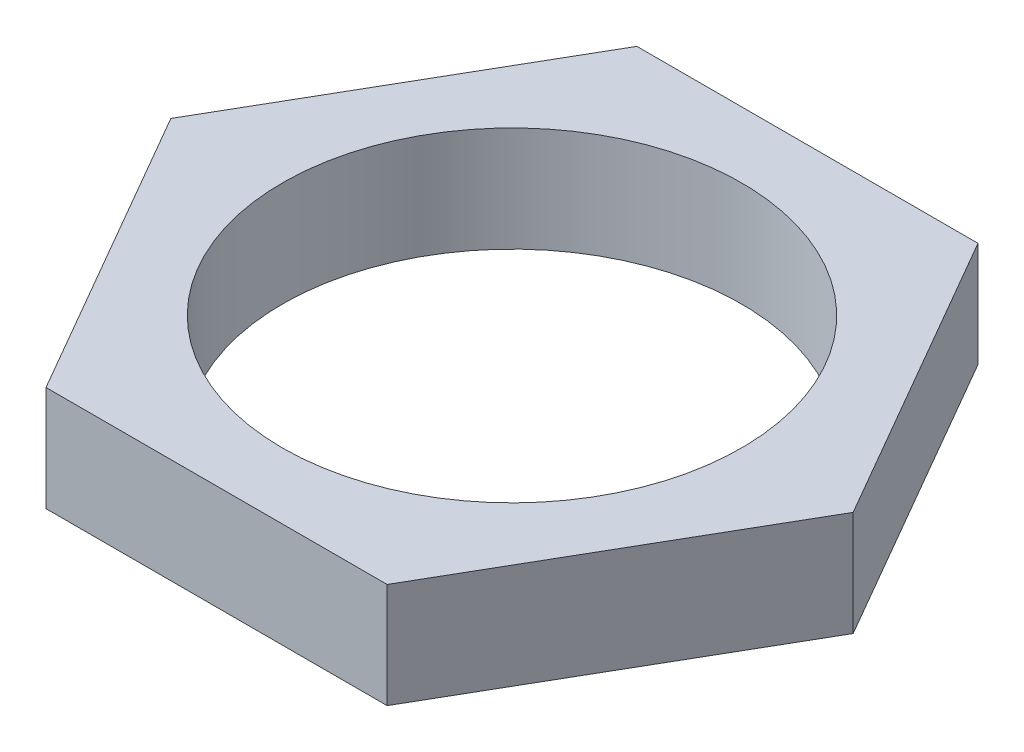
SolidWorks part; units mm, degrees
material "6061-T6 (SS)"
ref_plane "Front Plane" through (0, 0, 0) normal (0, 0, 1) x (1, 0, 0)
ref_plane "Top Plane" through (0, 0, 0) normal (0, 1, 0) x (1, 0, 0)
ref_plane "Right Plane" through (0, 0, 0) normal (1, 0, 0) x (0, 0, -1)
sketch "Sketch1" plane through (0, 0, 0) normal (0, 1, 0) x (1, 0, 0)
  line L1 (4.1275, -7.149) -> (8.255, 0)
  line L2 (8.255, 0) -> (4.1275, 7.149)
  line L3 (4.1275, 7.149) -> (-4.1275, 7.149)
  line L4 (-4.1275, 7.149) -> (-8.255, 0)
  line L5 (-8.255, 0) -> (-4.1275, -7.149)
  line L6 (-4.1275, -7.149) -> (4.1275, -7.149)
  circle A0 centre (0, 0) radius 7.149 construction
  circle A1 centre (0, 0) radius 5.5562
  dimension "D1" = 11.1125
  dimension "D2" = 16.51
extrude "Boss-Extrude1" add sketch "Sketch1" along normal blind 2.54
